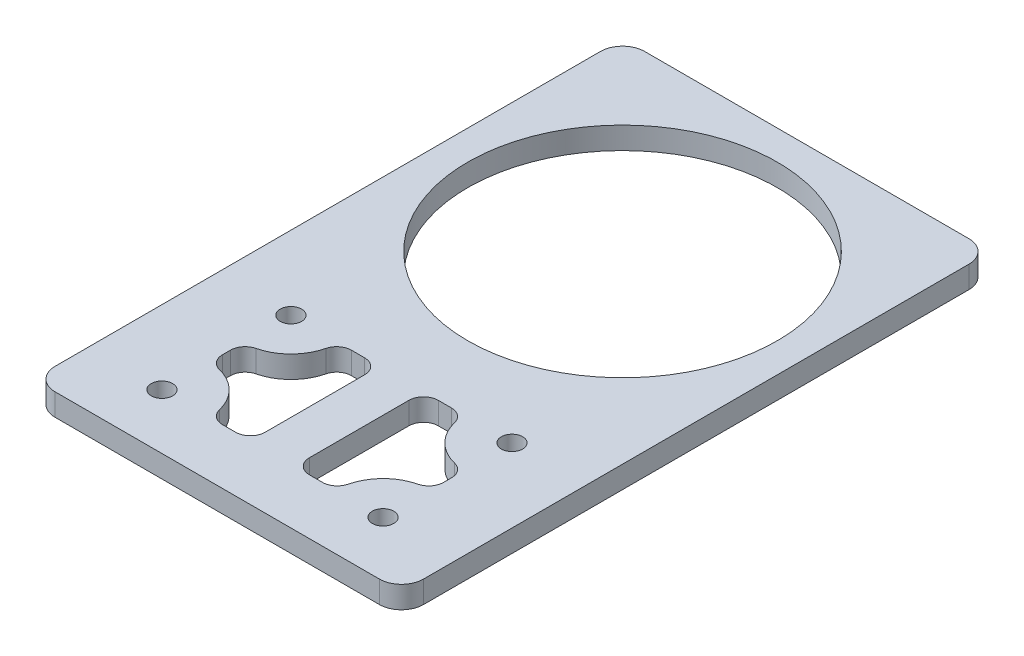
SolidWorks part; units mm, degrees
material "Thornel Mat VMA"
ref_plane "前视基准面" through (0, 0, 0) normal (0, 0, 1) x (1, 0, 0)
ref_plane "上视基准面" through (0, 0, 0) normal (0, 1, 0) x (1, 0, 0)
ref_plane "右视基准面" through (0, 0, 0) normal (1, 0, 0) x (0, 0, -1)
other "Configuration Table"
sketch "草图1" plane through (0, 0, 0) normal (0, 1, 0) x (1, 0, 0)
  line L1 (-25, -25) -> (25, -25)
  line L2 (-25, -25) -> (-25, 25)
  line L3 (-25, 25) -> (25, 25)
  line L4 (25, -25) -> (25, 25)
  line L5 (-25, -25) -> (25, 25) construction
  line L6 (-25, 25) -> (25, -25) construction
  circle A0 centre (0, 0) radius 21
  dimension "D1" = 42
  dimension "D2" = 50
  dimension "D3" = 50
extrude "凸台-拉伸1" add sketch "草图1" along normal blind 3
sketch "草图2" plane through (0, 3, 0) normal (0, 1, 0) x (1, 0, 0)
  line L1 (-25, -40) -> (25, -40) construction
  line L2 (-25, -40) -> (-25, -55)
  line L3 (-25, -55) -> (25, -55)
  line L4 (25, -40) -> (25, -55)
  line L5 (-25, -47.5) -> (25, -47.5) construction
  line L6 (25, -25) -> (25, 25) construction
  line L7 (-25, -25) -> (25, -25)
  line L9 (-25, -40) -> (25, -40) construction
  line L11 (-25, -25) -> (25, -25)
  line L12 (-25, -25) -> (-25, -40)
  line L13 (-25, -40) -> (25, -40) construction
  line L14 (25, -25) -> (25, -40)
  circle A0 centre (-15, -47.5) radius 1.45
  circle A1 centre (15, -47.5) radius 1.45
  dimension "D2" = 2.9
  dimension "D3" = 2.9
  dimension "D4" = 10
  dimension "D1" = 15
  dimension "D5" = 10
  dimension "D6" = 40
extrude "凸台-拉伸2" add sketch "草图2" against normal up to surface (3 mm away)
fillet "圆角1" radius 3 4 edges at (25, 1.5, 55) (-25, 1.5, 55) (25, 1.5, -25) (-25, 1.5, -25)
sketch "草图3" plane through (0, 3, 0) normal (0, 1, 0) x (1, 0, 0)
  line L0 (0, 0) -> (0, -55) construction
  line L1 (-22, -55) -> (22, -55) construction
  line L2 (-15, -30) -> (15, -30) construction
  circle A0 centre (-15, -30) radius 1.45
  circle A1 centre (15, -30) radius 1.45
  dimension "D4" = 2.9
  dimension "D5" = 2.9
  dimension "D1" = 15
  dimension "D2" = 15
  dimension "D3" = 25
extrude "切除-拉伸1" cut sketch "草图3" against normal through all
sketch "草图12" plane through (0, 3, 0) normal (0, 1, 0) x (1, 0, 0)
  line L0 (-15, -36.45) -> (-15, -41.05)
  line L1 (-8.55, -30) -> (8.55, -30)
  line L2 (15, -36.45) -> (15, -41.05)
  line L3 (-8.55, -47.5) -> (8.55, -47.5)
  circle A0 centre (-15, -30) radius 6.45
  circle A1 centre (-15, -47.5) radius 1.45
  circle A2 centre (-15, -47.5) radius 1.45
  circle A3 centre (15, -47.5) radius 1.45
  circle A4 centre (15, -47.5) radius 1.45
  circle A5 centre (0, 0) radius 21
  circle A6 centre (0, 0) radius 21
  circle A7 centre (15, -30) radius 1.45
  circle A8 centre (15, -30) radius 1.45
  circle A9 centre (-15, -30) radius 1.45
  circle A10 centre (-15, -30) radius 1.45
  circle A11 centre (15, -30) radius 6.45
  circle A12 centre (-15, -47.5) radius 6.45
  circle A13 centre (15, -47.5) radius 6.45
  dimension "D1" = 0
  dimension "D2" = 0
  dimension "D3" = 0
  dimension "D4" = 0
  dimension "D5" = 0
  dimension "D6" = 5
extrude "切除-拉伸7" cut sketch "草图12" against normal through all contours A13 L2 A11 L1 A0 L0 A12 L3
sketch "草图13" plane through (0, 3, 0) normal (0, 1, 0) x (1, 0, 0)
  line L0 (0, -30) -> (0, -47.5) construction
  line L1 (-8.55, -30) -> (8.55, -30) construction
  line L2 (-8.55, -47.5) -> (8.55, -47.5) construction
  line L3 (-3, -30) -> (-3, -47.5)
  line L4 (3, -30) -> (3, -47.5)
  line L5 (-3, -30) -> (3, -30)
  line L6 (3, -47.5) -> (-3, -47.5)
  dimension "D1" = 3
  dimension "D2" = 3
extrude "凸台-拉伸3" add sketch "草图13" against normal blind 3
fillet "圆角2" radius 2 12 edges at (8.55, 1.5, 30) (15, 1.5, 36.45) (15, 1.5, 41.05) (8.55, 1.5, 47.5) (3, 1.5, 47.5) (3, 1.5, 30) (-8.55, 1.5, 47.5) (-15, 1.5, 41.05) (-15, 1.5, 36.45) (-3, 1.5, 30) (-3, 1.5, 47.5) (-8.55, 1.5, 30)
